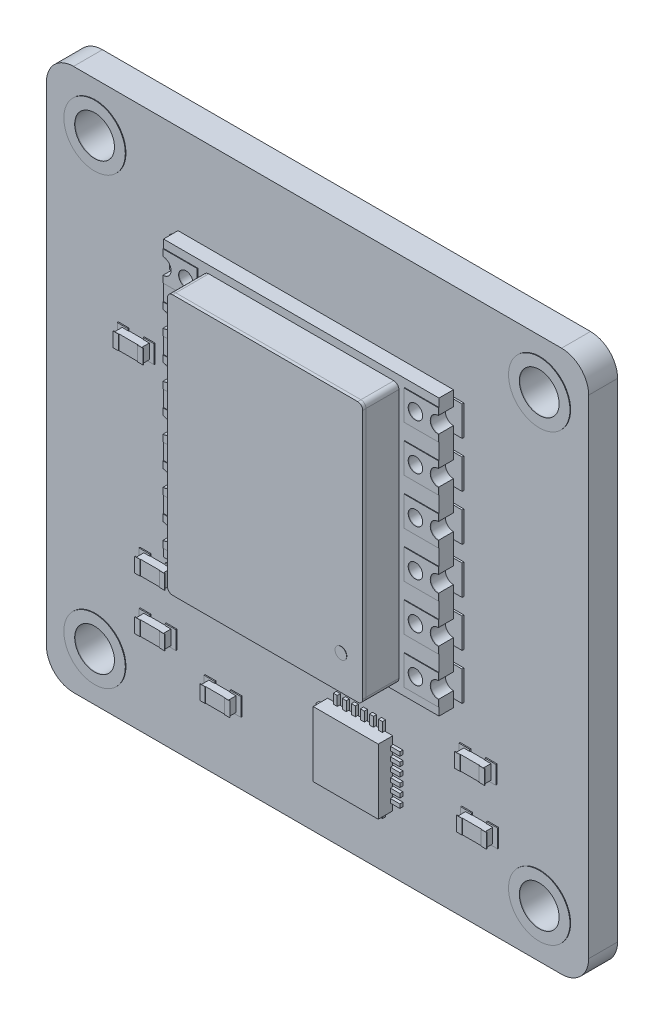
SolidWorks part; units mm, degrees
ref_plane "前视基准面" through (0, 0, 0) normal (0, 0, 1) x (1, 0, 0)
ref_plane "上视基准面" through (0, 0, 0) normal (0, 1, 0) x (1, 0, 0)
ref_plane "右视基准面" through (0, 0, 0) normal (1, 0, 0) x (0, 0, -1)
other "Configuration Table"
sketch "载板PCB_30x30x1.6_四孔D2.2_孔距24.6_草图" plane through (0, 0, 0) normal (0, 0, 1) x (1, 0, 0)
  line L0 (-13.5, -15) -> (13.5, -15)
  line L1 (15, -13.5) -> (15, 13.5)
  line L2 (13.5, 15) -> (-13.5, 15)
  line L3 (-15, 13.5) -> (-15, -13.5)
  arc A0 (13.5, -15) -> (15, -13.5) centre (13.5, -13.5) ccw
  arc A1 (15, 13.5) -> (13.5, 15) centre (13.5, 13.5) ccw
  arc A2 (-13.5, 15) -> (-15, 13.5) centre (-13.5, 13.5) ccw
  arc A3 (-15, -13.5) -> (-13.5, -15) centre (-13.5, -13.5) ccw
  circle A4 centre (-12.3, -12.3) radius 1.1
  circle A5 centre (-12.3, 12.3) radius 1.1
  circle A6 centre (12.3, -12.3) radius 1.1
  circle A7 centre (12.3, 12.3) radius 1.1
extrude "载板PCB_30x30x1.6_四孔D2.2_孔距24.6" add sketch "载板PCB_30x30x1.6_四孔D2.2_孔距24.6_草图" along normal blind 1.6 separate body
sketch "载板安装孔镀锡环_草图" plane through (0, 0, 0) normal (0, 0, 1) x (1, 0, 0)
  circle A0 centre (-12.3, -12.3) radius 1.7
  circle A1 centre (-12.3, -12.3) radius 1.1
  circle A2 centre (-12.3, 12.3) radius 1.7
  circle A3 centre (-12.3, 12.3) radius 1.1
  circle A4 centre (12.3, -12.3) radius 1.7
  circle A5 centre (12.3, -12.3) radius 1.1
  circle A6 centre (12.3, 12.3) radius 1.7
  circle A7 centre (12.3, 12.3) radius 1.1
extrude "载板安装孔镀锡环" add sketch "载板安装孔镀锡环_草图" along normal blind 0.035 from offset 1.6 separate body
sketch "载板12处焊接焊盘_间距2.54_草图" plane through (0, 0, 0) normal (0, 0, 1) x (1, 0, 0)
  line L1 (-8.1, -4.675) -> (-5.6, -4.675)
  line L2 (-8.1, -4.675) -> (-8.1, -3.025)
  line L3 (-8.1, -3.025) -> (-5.6, -3.025)
  line L4 (-5.6, -4.675) -> (-5.6, -3.025)
  line L6 (-8.1, -2.135) -> (-5.6, -2.135)
  line L7 (-8.1, -2.135) -> (-8.1, -0.485)
  line L8 (-8.1, -0.485) -> (-5.6, -0.485)
  line L9 (-5.6, -2.135) -> (-5.6, -0.485)
  line L11 (-8.1, 0.405) -> (-5.6, 0.405)
  line L12 (-8.1, 0.405) -> (-8.1, 2.055)
  line L13 (-8.1, 2.055) -> (-5.6, 2.055)
  line L14 (-5.6, 0.405) -> (-5.6, 2.055)
  line L16 (-8.1, 2.945) -> (-5.6, 2.945)
  line L17 (-8.1, 2.945) -> (-8.1, 4.595)
  line L18 (-8.1, 4.595) -> (-5.6, 4.595)
  line L19 (-5.6, 2.945) -> (-5.6, 4.595)
  line L21 (-8.1, 5.485) -> (-5.6, 5.485)
  line L22 (-8.1, 5.485) -> (-8.1, 7.135)
  line L23 (-8.1, 7.135) -> (-5.6, 7.135)
  line L24 (-5.6, 5.485) -> (-5.6, 7.135)
  line L26 (-8.1, 8.025) -> (-5.6, 8.025)
  line L27 (-8.1, 8.025) -> (-8.1, 9.675)
  line L28 (-8.1, 9.675) -> (-5.6, 9.675)
  line L29 (-5.6, 8.025) -> (-5.6, 9.675)
  line L31 (5.6, -4.675) -> (8.1, -4.675)
  line L32 (5.6, -4.675) -> (5.6, -3.025)
  line L33 (5.6, -3.025) -> (8.1, -3.025)
  line L34 (8.1, -4.675) -> (8.1, -3.025)
  line L36 (5.6, -2.135) -> (8.1, -2.135)
  line L37 (5.6, -2.135) -> (5.6, -0.485)
  line L38 (5.6, -0.485) -> (8.1, -0.485)
  line L39 (8.1, -2.135) -> (8.1, -0.485)
  line L41 (5.6, 0.405) -> (8.1, 0.405)
  line L42 (5.6, 0.405) -> (5.6, 2.055)
  line L43 (5.6, 2.055) -> (8.1, 2.055)
  line L44 (8.1, 0.405) -> (8.1, 2.055)
  line L46 (5.6, 2.945) -> (8.1, 2.945)
  line L47 (5.6, 2.945) -> (5.6, 4.595)
  line L48 (5.6, 4.595) -> (8.1, 4.595)
  line L49 (8.1, 2.945) -> (8.1, 4.595)
  line L51 (5.6, 5.485) -> (8.1, 5.485)
  line L52 (5.6, 5.485) -> (5.6, 7.135)
  line L53 (5.6, 7.135) -> (8.1, 7.135)
  line L54 (8.1, 5.485) -> (8.1, 7.135)
  line L56 (5.6, 8.025) -> (8.1, 8.025)
  line L57 (5.6, 8.025) -> (5.6, 9.675)
  line L58 (5.6, 9.675) -> (8.1, 9.675)
  line L59 (8.1, 8.025) -> (8.1, 9.675)
extrude "载板12处焊接焊盘_间距2.54" add sketch "载板12处焊接焊盘_间距2.54_草图" along normal blind 0.1 from offset 1.6 separate body
sketch "陀螺仪模块PCB_15.24x15.24x0.8_双侧半孔_草图" plane through (0, 0, 0) normal (0, 0, 1) x (1, 0, 0)
  line L0 (-7.62, -5.12) -> (7.62, -5.12)
  line L1 (7.62, -5.12) -> (7.62, -4.3)
  line L2 (7.62, -3.4) -> (7.62, -1.76)
  line L3 (7.62, -0.86) -> (7.62, 0.78)
  line L4 (7.62, 1.68) -> (7.62, 3.32)
  line L5 (7.62, 4.22) -> (7.62, 5.86)
  line L6 (7.62, 6.76) -> (7.62, 8.4)
  line L7 (7.62, 9.3) -> (7.62, 10.12)
  line L8 (7.62, 10.12) -> (-7.62, 10.12)
  line L9 (-7.62, 10.12) -> (-7.62, 9.3)
  line L10 (-7.62, 8.4) -> (-7.62, 6.76)
  line L11 (-7.62, 5.86) -> (-7.62, 4.22)
  line L12 (-7.62, 3.32) -> (-7.62, 1.68)
  line L13 (-7.62, 0.78) -> (-7.62, -0.86)
  line L14 (-7.62, -1.76) -> (-7.62, -3.4)
  line L15 (-7.62, -4.3) -> (-7.62, -5.12)
  arc A0 (7.62, -4.3) -> (7.62, -3.4) centre (7.62, -3.85) cw
  arc A1 (7.62, -1.76) -> (7.62, -0.86) centre (7.62, -1.31) cw
  arc A2 (7.62, 0.78) -> (7.62, 1.68) centre (7.62, 1.23) cw
  arc A3 (7.62, 3.32) -> (7.62, 4.22) centre (7.62, 3.77) cw
  arc A4 (7.62, 5.86) -> (7.62, 6.76) centre (7.62, 6.31) cw
  arc A5 (7.62, 8.4) -> (7.62, 9.3) centre (7.62, 8.85) cw
  arc A6 (-7.62, 9.3) -> (-7.62, 8.4) centre (-7.62, 8.85) cw
  arc A7 (-7.62, 6.76) -> (-7.62, 5.86) centre (-7.62, 6.31) cw
  arc A8 (-7.62, 4.22) -> (-7.62, 3.32) centre (-7.62, 3.77) cw
  arc A9 (-7.62, 1.68) -> (-7.62, 0.78) centre (-7.62, 1.23) cw
  arc A10 (-7.62, -0.86) -> (-7.62, -1.76) centre (-7.62, -1.31) cw
  arc A11 (-7.62, -3.4) -> (-7.62, -4.3) centre (-7.62, -3.85) cw
extrude "陀螺仪模块PCB_15.24x15.24x0.8_双侧半孔" add sketch "陀螺仪模块PCB_15.24x15.24x0.8_双侧半孔_草图" along normal blind 0.8 from offset 1.7 separate body
sketch "模块12处半孔镀锡焊盘_草图" plane through (0, 0, 0) normal (0, 0, 1) x (1, 0, 0)
  line L0 (-5.72, -4.67) -> (-5.72, -3.03)
  line L1 (-5.72, -3.03) -> (-7.62, -3.03)
  line L2 (-7.62, -3.03) -> (-7.62, -3.4)
  line L3 (-7.62, -4.3) -> (-7.62, -4.67)
  line L4 (-7.62, -4.67) -> (-5.72, -4.67)
  line L5 (-5.72, -2.13) -> (-5.72, -0.49)
  line L6 (-5.72, -0.49) -> (-7.62, -0.49)
  line L7 (-7.62, -0.49) -> (-7.62, -0.86)
  line L8 (-7.62, -1.76) -> (-7.62, -2.13)
  line L9 (-7.62, -2.13) -> (-5.72, -2.13)
  line L10 (-5.72, 0.41) -> (-5.72, 2.05)
  line L11 (-5.72, 2.05) -> (-7.62, 2.05)
  line L12 (-7.62, 2.05) -> (-7.62, 1.68)
  line L13 (-7.62, 0.78) -> (-7.62, 0.41)
  line L14 (-7.62, 0.41) -> (-5.72, 0.41)
  line L15 (-5.72, 2.95) -> (-5.72, 4.59)
  line L16 (-5.72, 4.59) -> (-7.62, 4.59)
  line L17 (-7.62, 4.59) -> (-7.62, 4.22)
  line L18 (-7.62, 3.32) -> (-7.62, 2.95)
  line L19 (-7.62, 2.95) -> (-5.72, 2.95)
  line L20 (-5.72, 5.49) -> (-5.72, 7.13)
  line L21 (-5.72, 7.13) -> (-7.62, 7.13)
  line L22 (-7.62, 7.13) -> (-7.62, 6.76)
  line L23 (-7.62, 5.86) -> (-7.62, 5.49)
  line L24 (-7.62, 5.49) -> (-5.72, 5.49)
  line L25 (-5.72, 8.03) -> (-5.72, 9.67)
  line L26 (-5.72, 9.67) -> (-7.62, 9.67)
  line L27 (-7.62, 9.67) -> (-7.62, 9.3)
  line L28 (-7.62, 8.4) -> (-7.62, 8.03)
  line L29 (-7.62, 8.03) -> (-5.72, 8.03)
  line L30 (5.72, -4.67) -> (7.62, -4.67)
  line L31 (7.62, -4.67) -> (7.62, -4.3)
  line L32 (7.62, -3.4) -> (7.62, -3.03)
  line L33 (7.62, -3.03) -> (5.72, -3.03)
  line L34 (5.72, -3.03) -> (5.72, -4.67)
  line L35 (5.72, -2.13) -> (7.62, -2.13)
  line L36 (7.62, -2.13) -> (7.62, -1.76)
  line L37 (7.62, -0.86) -> (7.62, -0.49)
  line L38 (7.62, -0.49) -> (5.72, -0.49)
  line L39 (5.72, -0.49) -> (5.72, -2.13)
  line L40 (5.72, 0.41) -> (7.62, 0.41)
  line L41 (7.62, 0.41) -> (7.62, 0.78)
  line L42 (7.62, 1.68) -> (7.62, 2.05)
  line L43 (7.62, 2.05) -> (5.72, 2.05)
  line L44 (5.72, 2.05) -> (5.72, 0.41)
  line L45 (5.72, 2.95) -> (7.62, 2.95)
  line L46 (7.62, 2.95) -> (7.62, 3.32)
  line L47 (7.62, 4.22) -> (7.62, 4.59)
  line L48 (7.62, 4.59) -> (5.72, 4.59)
  line L49 (5.72, 4.59) -> (5.72, 2.95)
  line L50 (5.72, 5.49) -> (7.62, 5.49)
  line L51 (7.62, 5.49) -> (7.62, 5.86)
  line L52 (7.62, 6.76) -> (7.62, 7.13)
  line L53 (7.62, 7.13) -> (5.72, 7.13)
  line L54 (5.72, 7.13) -> (5.72, 5.49)
  line L55 (5.72, 8.03) -> (7.62, 8.03)
  line L56 (7.62, 8.03) -> (7.62, 8.4)
  line L57 (7.62, 9.3) -> (7.62, 9.67)
  line L58 (7.62, 9.67) -> (5.72, 9.67)
  line L59 (5.72, 9.67) -> (5.72, 8.03)
  arc A0 (-7.62, -3.4) -> (-7.62, -4.3) centre (-7.62, -3.85) cw
  arc A1 (-7.62, -0.86) -> (-7.62, -1.76) centre (-7.62, -1.31) cw
  arc A2 (-7.62, 1.68) -> (-7.62, 0.78) centre (-7.62, 1.23) cw
  arc A3 (-7.62, 4.22) -> (-7.62, 3.32) centre (-7.62, 3.77) cw
  arc A4 (-7.62, 6.76) -> (-7.62, 5.86) centre (-7.62, 6.31) cw
  arc A5 (-7.62, 9.3) -> (-7.62, 8.4) centre (-7.62, 8.85) cw
  arc A6 (7.62, -4.3) -> (7.62, -3.4) centre (7.62, -3.85) cw
  arc A7 (7.62, -1.76) -> (7.62, -0.86) centre (7.62, -1.31) cw
  arc A8 (7.62, 0.78) -> (7.62, 1.68) centre (7.62, 1.23) cw
  arc A9 (7.62, 3.32) -> (7.62, 4.22) centre (7.62, 3.77) cw
  arc A10 (7.62, 5.86) -> (7.62, 6.76) centre (7.62, 6.31) cw
  arc A11 (7.62, 8.4) -> (7.62, 9.3) centre (7.62, 8.85) cw
extrude "模块12处半孔镀锡焊盘" add sketch "模块12处半孔镀锡焊盘_草图" along normal blind 0.035 from offset 2.5 separate body
sketch "屏蔽罩侧壁_厚0.18_草图" plane through (0, 0, 0) normal (0, 0, 1) x (1, 0, 0)
  line L0 (-5.12, -4.7) -> (5.12, -4.7)
  line L1 (5.4, -4.42) -> (5.4, 9.42)
  line L2 (5.12, 9.7) -> (-5.12, 9.7)
  line L3 (-5.4, 9.42) -> (-5.4, -4.42)
  line L4 (-5.12, -4.52) -> (5.12, -4.52)
  line L5 (5.22, -4.42) -> (5.22, 9.42)
  line L6 (5.12, 9.52) -> (-5.12, 9.52)
  line L7 (-5.22, 9.42) -> (-5.22, -4.42)
  arc A0 (5.12, -4.7) -> (5.4, -4.42) centre (5.12, -4.42) ccw
  arc A1 (5.4, 9.42) -> (5.12, 9.7) centre (5.12, 9.42) ccw
  arc A2 (-5.12, 9.7) -> (-5.4, 9.42) centre (-5.12, 9.42) ccw
  arc A3 (-5.4, -4.42) -> (-5.12, -4.7) centre (-5.12, -4.42) ccw
  arc A4 (5.12, -4.52) -> (5.22, -4.42) centre (5.12, -4.42) ccw
  arc A5 (5.22, 9.42) -> (5.12, 9.52) centre (5.12, 9.42) ccw
  arc A6 (-5.12, 9.52) -> (-5.22, 9.42) centre (-5.12, 9.42) ccw
  arc A7 (-5.22, -4.42) -> (-5.12, -4.52) centre (-5.12, -4.42) ccw
extrude "屏蔽罩侧壁_厚0.18" add sketch "屏蔽罩侧壁_厚0.18_草图" along normal blind 1.82 from offset 2.5 separate body
sketch "屏蔽罩顶盖_厚0.18_模块总高2.8_草图" plane through (0, 0, 0) normal (0, 0, 1) x (1, 0, 0)
  line L0 (-5.12, -4.7) -> (5.12, -4.7)
  line L1 (5.4, -4.42) -> (5.4, 9.42)
  line L2 (5.12, 9.7) -> (-5.12, 9.7)
  line L3 (-5.4, 9.42) -> (-5.4, -4.42)
  arc A0 (5.12, -4.7) -> (5.4, -4.42) centre (5.12, -4.42) ccw
  arc A1 (5.4, 9.42) -> (5.12, 9.7) centre (5.12, 9.42) ccw
  arc A2 (-5.12, 9.7) -> (-5.4, 9.42) centre (-5.12, 9.42) ccw
  arc A3 (-5.4, -4.42) -> (-5.12, -4.7) centre (-5.12, -4.42) ccw
extrude "屏蔽罩顶盖_厚0.18_模块总高2.8" add sketch "屏蔽罩顶盖_厚0.18_模块总高2.8_草图" along normal blind 0.18 from offset 4.32 separate body
sketch "屏蔽罩定位标记_草图" plane through (0, 0, 0) normal (0, 0, 1) x (1, 0, 0)
  circle A0 centre (4.2, -2.8) radius 0.32
extrude "屏蔽罩定位标记" add sketch "屏蔽罩定位标记_草图" along normal blind 0.012 from offset 4.5 separate body
sketch "载板控制芯片_4x4_草图" plane through (0, 0, 0) normal (0, 0, 1) x (1, 0, 0)
  line L1 (0.6, -11.8) -> (4.2, -11.8)
  line L2 (0.6, -11.8) -> (0.6, -8.2)
  line L3 (0.6, -8.2) -> (4.2, -8.2)
  line L4 (4.2, -11.8) -> (4.2, -8.2)
extrude "载板控制芯片_4x4" add sketch "载板控制芯片_4x4_草图" along normal blind 0.8 from offset 1.64 separate body
sketch "载板控制芯片24引脚_草图" plane through (0, 0, 0) normal (0, 0, 1) x (1, 0, 0)
  line L1 (1.04, -12.325) -> (1.26, -12.325)
  line L2 (1.04, -12.325) -> (1.04, -11.775)
  line L3 (1.04, -11.775) -> (1.26, -11.775)
  line L4 (1.26, -12.325) -> (1.26, -11.775)
  line L6 (1.04, -8.225) -> (1.26, -8.225)
  line L7 (1.04, -8.225) -> (1.04, -7.675)
  line L8 (1.04, -7.675) -> (1.26, -7.675)
  line L9 (1.26, -8.225) -> (1.26, -7.675)
  line L11 (0.075, -11.36) -> (0.625, -11.36)
  line L12 (0.075, -11.36) -> (0.075, -11.14)
  line L13 (0.075, -11.14) -> (0.625, -11.14)
  line L14 (0.625, -11.36) -> (0.625, -11.14)
  line L16 (4.175, -11.36) -> (4.725, -11.36)
  line L17 (4.175, -11.36) -> (4.175, -11.14)
  line L18 (4.175, -11.14) -> (4.725, -11.14)
  line L19 (4.725, -11.36) -> (4.725, -11.14)
  line L21 (1.54, -12.325) -> (1.76, -12.325)
  line L22 (1.54, -12.325) -> (1.54, -11.775)
  line L23 (1.54, -11.775) -> (1.76, -11.775)
  line L24 (1.76, -12.325) -> (1.76, -11.775)
  line L26 (1.54, -8.225) -> (1.76, -8.225)
  line L27 (1.54, -8.225) -> (1.54, -7.675)
  line L28 (1.54, -7.675) -> (1.76, -7.675)
  line L29 (1.76, -8.225) -> (1.76, -7.675)
  line L31 (0.075, -10.86) -> (0.625, -10.86)
  line L32 (0.075, -10.86) -> (0.075, -10.64)
  line L33 (0.075, -10.64) -> (0.625, -10.64)
  line L34 (0.625, -10.86) -> (0.625, -10.64)
  line L36 (4.175, -10.86) -> (4.725, -10.86)
  line L37 (4.175, -10.86) -> (4.175, -10.64)
  line L38 (4.175, -10.64) -> (4.725, -10.64)
  line L39 (4.725, -10.86) -> (4.725, -10.64)
  line L41 (2.04, -12.325) -> (2.26, -12.325)
  line L42 (2.04, -12.325) -> (2.04, -11.775)
  line L43 (2.04, -11.775) -> (2.26, -11.775)
  line L44 (2.26, -12.325) -> (2.26, -11.775)
  line L46 (2.04, -8.225) -> (2.26, -8.225)
  line L47 (2.04, -8.225) -> (2.04, -7.675)
  line L48 (2.04, -7.675) -> (2.26, -7.675)
  line L49 (2.26, -8.225) -> (2.26, -7.675)
  line L51 (0.075, -10.36) -> (0.625, -10.36)
  line L52 (0.075, -10.36) -> (0.075, -10.14)
  line L53 (0.075, -10.14) -> (0.625, -10.14)
  line L54 (0.625, -10.36) -> (0.625, -10.14)
  line L56 (4.175, -10.36) -> (4.725, -10.36)
  line L57 (4.175, -10.36) -> (4.175, -10.14)
  line L58 (4.175, -10.14) -> (4.725, -10.14)
  line L59 (4.725, -10.36) -> (4.725, -10.14)
  line L61 (2.54, -12.325) -> (2.76, -12.325)
  line L62 (2.54, -12.325) -> (2.54, -11.775)
  line L63 (2.54, -11.775) -> (2.76, -11.775)
  line L64 (2.76, -12.325) -> (2.76, -11.775)
  line L66 (2.54, -8.225) -> (2.76, -8.225)
  line L67 (2.54, -8.225) -> (2.54, -7.675)
  line L68 (2.54, -7.675) -> (2.76, -7.675)
  line L69 (2.76, -8.225) -> (2.76, -7.675)
  line L71 (0.075, -9.86) -> (0.625, -9.86)
  line L72 (0.075, -9.86) -> (0.075, -9.64)
  line L73 (0.075, -9.64) -> (0.625, -9.64)
  line L74 (0.625, -9.86) -> (0.625, -9.64)
  line L76 (4.175, -9.86) -> (4.725, -9.86)
  line L77 (4.175, -9.86) -> (4.175, -9.64)
  line L78 (4.175, -9.64) -> (4.725, -9.64)
  line L79 (4.725, -9.86) -> (4.725, -9.64)
  line L81 (3.04, -12.325) -> (3.26, -12.325)
  line L82 (3.04, -12.325) -> (3.04, -11.775)
  line L83 (3.04, -11.775) -> (3.26, -11.775)
  line L84 (3.26, -12.325) -> (3.26, -11.775)
  line L86 (3.04, -8.225) -> (3.26, -8.225)
  line L87 (3.04, -8.225) -> (3.04, -7.675)
  line L88 (3.04, -7.675) -> (3.26, -7.675)
  line L89 (3.26, -8.225) -> (3.26, -7.675)
  line L91 (0.075, -9.36) -> (0.625, -9.36)
  line L92 (0.075, -9.36) -> (0.075, -9.14)
  line L93 (0.075, -9.14) -> (0.625, -9.14)
  line L94 (0.625, -9.36) -> (0.625, -9.14)
  line L96 (4.175, -9.36) -> (4.725, -9.36)
  line L97 (4.175, -9.36) -> (4.175, -9.14)
  line L98 (4.175, -9.14) -> (4.725, -9.14)
  line L99 (4.725, -9.36) -> (4.725, -9.14)
  line L101 (3.54, -12.325) -> (3.76, -12.325)
  line L102 (3.54, -12.325) -> (3.54, -11.775)
  line L103 (3.54, -11.775) -> (3.76, -11.775)
  line L104 (3.76, -12.325) -> (3.76, -11.775)
  line L106 (3.54, -8.225) -> (3.76, -8.225)
  line L107 (3.54, -8.225) -> (3.54, -7.675)
  line L108 (3.54, -7.675) -> (3.76, -7.675)
  line L109 (3.76, -8.225) -> (3.76, -7.675)
  line L111 (0.075, -8.86) -> (0.625, -8.86)
  line L112 (0.075, -8.86) -> (0.075, -8.64)
  line L113 (0.075, -8.64) -> (0.625, -8.64)
  line L114 (0.625, -8.86) -> (0.625, -8.64)
  line L116 (4.175, -8.86) -> (4.725, -8.86)
  line L117 (4.175, -8.86) -> (4.175, -8.64)
  line L118 (4.175, -8.64) -> (4.725, -8.64)
  line L119 (4.725, -8.86) -> (4.725, -8.64)
extrude "载板控制芯片24引脚" add sketch "载板控制芯片24引脚_草图" along normal blind 0.17 from offset 1.6 separate body
sketch "载板贴片元件焊盘_草图" plane through (0, 0, 0) normal (0, 0, 1) x (1, 0, 0)
  line L1 (-9.82, -10.1) -> (-9.22, -10.1)
  line L2 (-9.82, -10.1) -> (-9.82, -9.1)
  line L3 (-9.82, -9.1) -> (-9.22, -9.1)
  line L4 (-9.22, -10.1) -> (-9.22, -9.1)
  line L6 (-8.38, -10.1) -> (-7.78, -10.1)
  line L7 (-8.38, -10.1) -> (-8.38, -9.1)
  line L8 (-8.38, -9.1) -> (-7.78, -9.1)
  line L9 (-7.78, -10.1) -> (-7.78, -9.1)
  line L11 (-9.82, -7.2) -> (-9.22, -7.2)
  line L12 (-9.82, -7.2) -> (-9.82, -6.2)
  line L13 (-9.82, -6.2) -> (-9.22, -6.2)
  line L14 (-9.22, -7.2) -> (-9.22, -6.2)
  line L16 (-8.38, -7.2) -> (-7.78, -7.2)
  line L17 (-8.38, -7.2) -> (-8.38, -6.2)
  line L18 (-8.38, -6.2) -> (-7.78, -6.2)
  line L19 (-7.78, -7.2) -> (-7.78, -6.2)
  line L21 (-6.22, -11.5) -> (-5.62, -11.5)
  line L22 (-6.22, -11.5) -> (-6.22, -10.5)
  line L23 (-6.22, -10.5) -> (-5.62, -10.5)
  line L24 (-5.62, -11.5) -> (-5.62, -10.5)
  line L26 (-4.78, -11.5) -> (-4.18, -11.5)
  line L27 (-4.78, -11.5) -> (-4.78, -10.5)
  line L28 (-4.78, -10.5) -> (-4.18, -10.5)
  line L29 (-4.18, -11.5) -> (-4.18, -10.5)
  line L31 (7.88, -7.7) -> (8.48, -7.7)
  line L32 (7.88, -7.7) -> (7.88, -6.7)
  line L33 (7.88, -6.7) -> (8.48, -6.7)
  line L34 (8.48, -7.7) -> (8.48, -6.7)
  line L36 (9.32, -7.7) -> (9.92, -7.7)
  line L37 (9.32, -7.7) -> (9.32, -6.7)
  line L38 (9.32, -6.7) -> (9.92, -6.7)
  line L39 (9.92, -7.7) -> (9.92, -6.7)
  line L41 (7.98, -10.7) -> (8.58, -10.7)
  line L42 (7.98, -10.7) -> (7.98, -9.7)
  line L43 (7.98, -9.7) -> (8.58, -9.7)
  line L44 (8.58, -10.7) -> (8.58, -9.7)
  line L46 (9.42, -10.7) -> (10.02, -10.7)
  line L47 (9.42, -10.7) -> (9.42, -9.7)
  line L48 (9.42, -9.7) -> (10.02, -9.7)
  line L49 (10.02, -10.7) -> (10.02, -9.7)
  line L51 (-11.02, 3) -> (-10.42, 3)
  line L52 (-11.02, 3) -> (-11.02, 4)
  line L53 (-11.02, 4) -> (-10.42, 4)
  line L54 (-10.42, 3) -> (-10.42, 4)
  line L56 (-9.58, 3) -> (-8.98, 3)
  line L57 (-9.58, 3) -> (-9.58, 4)
  line L58 (-9.58, 4) -> (-8.98, 4)
  line L59 (-8.98, 3) -> (-8.98, 4)
extrude "载板贴片元件焊盘" add sketch "载板贴片元件焊盘_草图" along normal blind 0.06 from offset 1.6 separate body
sketch "贴片元件_1_草图" plane through (0, 0, 0) normal (0, 0, 1) x (1, 0, 0)
  line L1 (-9.55, -10) -> (-8.05, -10)
  line L2 (-9.55, -10) -> (-9.55, -9.2)
  line L3 (-9.55, -9.2) -> (-8.05, -9.2)
  line L4 (-8.05, -10) -> (-8.05, -9.2)
extrude "贴片元件_1" add sketch "贴片元件_1_草图" along normal blind 0.42 from offset 1.64 separate body
sketch "贴片元件_2_草图" plane through (0, 0, 0) normal (0, 0, 1) x (1, 0, 0)
  line L1 (-9.55, -7.1) -> (-8.05, -7.1)
  line L2 (-9.55, -7.1) -> (-9.55, -6.3)
  line L3 (-9.55, -6.3) -> (-8.05, -6.3)
  line L4 (-8.05, -7.1) -> (-8.05, -6.3)
extrude "贴片元件_2" add sketch "贴片元件_2_草图" along normal blind 0.42 from offset 1.64 separate body
sketch "贴片元件_3_草图" plane through (0, 0, 0) normal (0, 0, 1) x (1, 0, 0)
  line L1 (-5.95, -11.4) -> (-4.45, -11.4)
  line L2 (-5.95, -11.4) -> (-5.95, -10.6)
  line L3 (-5.95, -10.6) -> (-4.45, -10.6)
  line L4 (-4.45, -11.4) -> (-4.45, -10.6)
extrude "贴片元件_3" add sketch "贴片元件_3_草图" along normal blind 0.42 from offset 1.64 separate body
sketch "贴片元件_4_草图" plane through (0, 0, 0) normal (0, 0, 1) x (1, 0, 0)
  line L1 (8.15, -7.6) -> (9.65, -7.6)
  line L2 (8.15, -7.6) -> (8.15, -6.8)
  line L3 (8.15, -6.8) -> (9.65, -6.8)
  line L4 (9.65, -7.6) -> (9.65, -6.8)
extrude "贴片元件_4" add sketch "贴片元件_4_草图" along normal blind 0.42 from offset 1.64 separate body
sketch "贴片元件_5_草图" plane through (0, 0, 0) normal (0, 0, 1) x (1, 0, 0)
  line L1 (8.25, -10.6) -> (9.75, -10.6)
  line L2 (8.25, -10.6) -> (8.25, -9.8)
  line L3 (8.25, -9.8) -> (9.75, -9.8)
  line L4 (9.75, -10.6) -> (9.75, -9.8)
extrude "贴片元件_5" add sketch "贴片元件_5_草图" along normal blind 0.42 from offset 1.64 separate body
sketch "贴片元件_6_草图" plane through (0, 0, 0) normal (0, 0, 1) x (1, 0, 0)
  line L1 (-10.75, 3.1) -> (-9.25, 3.1)
  line L2 (-10.75, 3.1) -> (-10.75, 3.9)
  line L3 (-10.75, 3.9) -> (-9.25, 3.9)
  line L4 (-9.25, 3.1) -> (-9.25, 3.9)
extrude "贴片元件_6" add sketch "贴片元件_6_草图" along normal blind 0.42 from offset 1.64 separate body
sketch "贴片元件端电极_草图" plane through (0, 0, 0) normal (0, 0, 1) x (1, 0, 0)
  line L1 (-9.63, -10) -> (-9.33, -10)
  line L2 (-9.63, -10) -> (-9.63, -9.2)
  line L3 (-9.63, -9.2) -> (-9.33, -9.2)
  line L4 (-9.33, -10) -> (-9.33, -9.2)
  line L6 (-8.27, -10) -> (-7.97, -10)
  line L7 (-8.27, -10) -> (-8.27, -9.2)
  line L8 (-8.27, -9.2) -> (-7.97, -9.2)
  line L9 (-7.97, -10) -> (-7.97, -9.2)
  line L11 (-9.63, -7.1) -> (-9.33, -7.1)
  line L12 (-9.63, -7.1) -> (-9.63, -6.3)
  line L13 (-9.63, -6.3) -> (-9.33, -6.3)
  line L14 (-9.33, -7.1) -> (-9.33, -6.3)
  line L16 (-8.27, -7.1) -> (-7.97, -7.1)
  line L17 (-8.27, -7.1) -> (-8.27, -6.3)
  line L18 (-8.27, -6.3) -> (-7.97, -6.3)
  line L19 (-7.97, -7.1) -> (-7.97, -6.3)
  line L21 (-6.03, -11.4) -> (-5.73, -11.4)
  line L22 (-6.03, -11.4) -> (-6.03, -10.6)
  line L23 (-6.03, -10.6) -> (-5.73, -10.6)
  line L24 (-5.73, -11.4) -> (-5.73, -10.6)
  line L26 (-4.67, -11.4) -> (-4.37, -11.4)
  line L27 (-4.67, -11.4) -> (-4.67, -10.6)
  line L28 (-4.67, -10.6) -> (-4.37, -10.6)
  line L29 (-4.37, -11.4) -> (-4.37, -10.6)
  line L31 (8.07, -7.6) -> (8.37, -7.6)
  line L32 (8.07, -7.6) -> (8.07, -6.8)
  line L33 (8.07, -6.8) -> (8.37, -6.8)
  line L34 (8.37, -7.6) -> (8.37, -6.8)
  line L36 (9.43, -7.6) -> (9.73, -7.6)
  line L37 (9.43, -7.6) -> (9.43, -6.8)
  line L38 (9.43, -6.8) -> (9.73, -6.8)
  line L39 (9.73, -7.6) -> (9.73, -6.8)
  line L41 (8.17, -10.6) -> (8.47, -10.6)
  line L42 (8.17, -10.6) -> (8.17, -9.8)
  line L43 (8.17, -9.8) -> (8.47, -9.8)
  line L44 (8.47, -10.6) -> (8.47, -9.8)
  line L46 (9.53, -10.6) -> (9.83, -10.6)
  line L47 (9.53, -10.6) -> (9.53, -9.8)
  line L48 (9.53, -9.8) -> (9.83, -9.8)
  line L49 (9.83, -10.6) -> (9.83, -9.8)
  line L51 (-10.83, 3.1) -> (-10.53, 3.1)
  line L52 (-10.83, 3.1) -> (-10.83, 3.9)
  line L53 (-10.83, 3.9) -> (-10.53, 3.9)
  line L54 (-10.53, 3.1) -> (-10.53, 3.9)
  line L56 (-9.47, 3.1) -> (-9.17, 3.1)
  line L57 (-9.47, 3.1) -> (-9.47, 3.9)
  line L58 (-9.47, 3.9) -> (-9.17, 3.9)
  line L59 (-9.17, 3.1) -> (-9.17, 3.9)
extrude "贴片元件端电极" add sketch "贴片元件端电极_草图" along normal blind 0.025 from offset 2.06 separate body
sketch "完整引脚圆孔_12xD0.8_草图" plane through (0, 0, 0) normal (0, 0, 1) x (1, 0, 0)
  circle A0 centre (-6.35, -3.85) radius 0.4
  circle A1 centre (-6.35, -1.31) radius 0.4
  circle A2 centre (-6.35, 1.23) radius 0.4
  circle A3 centre (-6.35, 3.77) radius 0.4
  circle A4 centre (-6.35, 6.31) radius 0.4
  circle A5 centre (-6.35, 8.85) radius 0.4
  circle A6 centre (6.35, -3.85) radius 0.4
  circle A7 centre (6.35, -1.31) radius 0.4
  circle A8 centre (6.35, 1.23) radius 0.4
  circle A9 centre (6.35, 3.77) radius 0.4
  circle A10 centre (6.35, 6.31) radius 0.4
  circle A11 centre (6.35, 8.85) radius 0.4
extrude "12个完整引脚通孔_D0.8_排距12.7_间距2.54" cut sketch "完整引脚圆孔_12xD0.8_草图" against normal through all and the other way through all
